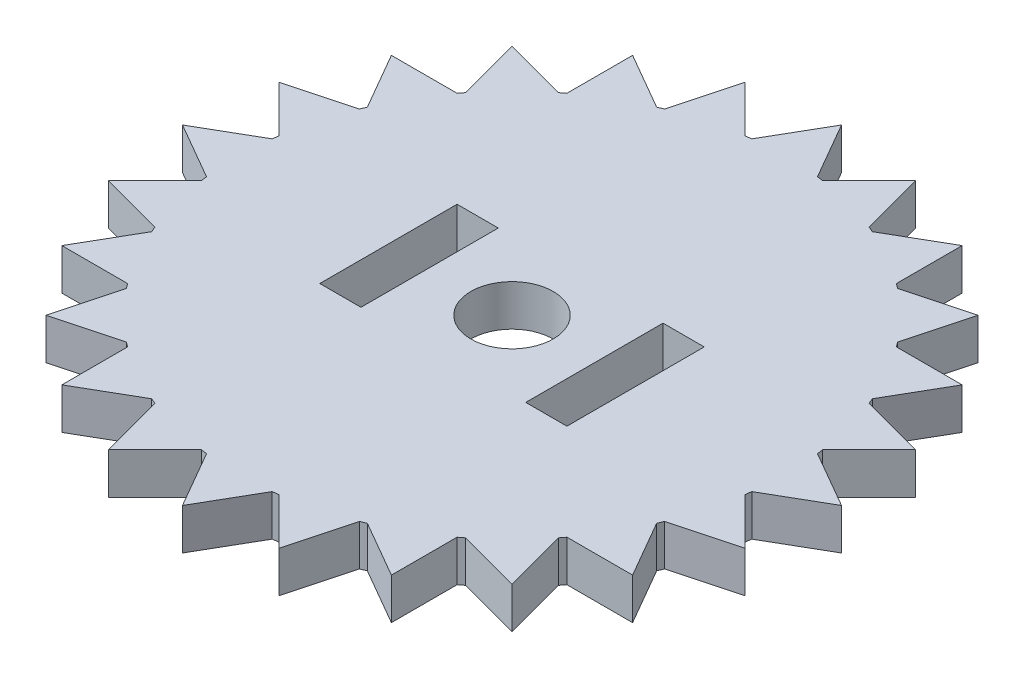
SolidWorks part; units mm, degrees
ref_plane "Front Plane" through (0, 0, 0) normal (0, 0, 1) x (1, 0, 0)
ref_plane "Top Plane" through (0, 0, 0) normal (0, 1, 0) x (1, 0, 0)
ref_plane "Right Plane" through (0, 0, 0) normal (1, 0, 0) x (0, 0, -1)
sketch "Sketch1" plane through (0, 0, 0) normal (0, 1, 0) x (1, 0, 0)
  circle A0 centre (0, 0) radius 20
  dimension "D1" = 40
extrude "Boss-Extrude1" add sketch "Sketch1" along normal blind 3
sketch "Sketch2" plane through (0, 3, 0) normal (0, 1, 0) x (1, 0, 0)
  line L0 (0, 20) -> (0, 24) construction
  line L24 (0, 24) -> (-2.3923, 19.8564)
  line L25 (-2.3923, 19.8564) -> (2.3923, 19.8564)
  line L26 (2.3923, 19.8564) -> (0, 24)
  circle A0 centre (0, 0) radius 20 construction
  point P55 (0, 0)
  dimension "D1" = 4
  dimension "D2" = 20
extrude "Boss-Extrude2" add sketch "Sketch2" against normal blind 3
pattern_circular "CirPattern1" count 24 over 360 about axis through (0, 0, 0) along (0, 1, 0) of "Boss-Extrude2"
sketch "Sketch3" plane through (0, 3, 0) normal (0, 1, 0) x (1, 0, 0)
  circle A0 centre (0, 0) radius 3
  dimension "D1" = 6
extrude "Cut-Extrude1" cut sketch "Sketch3" against normal blind 3
sketch "Sketch4" plane through (0, 3, 0) normal (0, 1, 0) x (1, 0, 0)
  line L1 (-9, -5) -> (-6, -5)
  line L2 (-9, -5) -> (-9, 5)
  line L3 (-9, 5) -> (-6, 5)
  line L4 (-6, -5) -> (-6, 5)
  line L5 (6, -5) -> (9, -5)
  line L6 (6, -5) -> (6, 5)
  line L7 (6, 5) -> (9, 5)
  line L8 (9, -5) -> (9, 5)
  point P4 (-6, 0)
  point P10 (6, 0)
  dimension "D1" = 3
  dimension "D2" = 10
  dimension "D3" = 6
  dimension "D4" = 3
  dimension "D5" = 10
  dimension "D6" = 6
extrude "Cut-Extrude2" cut sketch "Sketch4" against normal blind 10
equation "\"Big_Teeth\"= 24"
equation "\"Small_Teeth\"= 12"
equation "\"Kerf\"= 0mm"
equation "\"D1@Sketch4\"=3-\"Kerf\""
equation "\"D2@Sketch4\"=10-\"Kerf\""
equation "\"D4@Sketch4\"=\"D1@Sketch4\""
equation "\"D5@Sketch4\"=\"D2@Sketch4\""
equation "\"D6@Sketch4\"=\"D3@Sketch4\""
